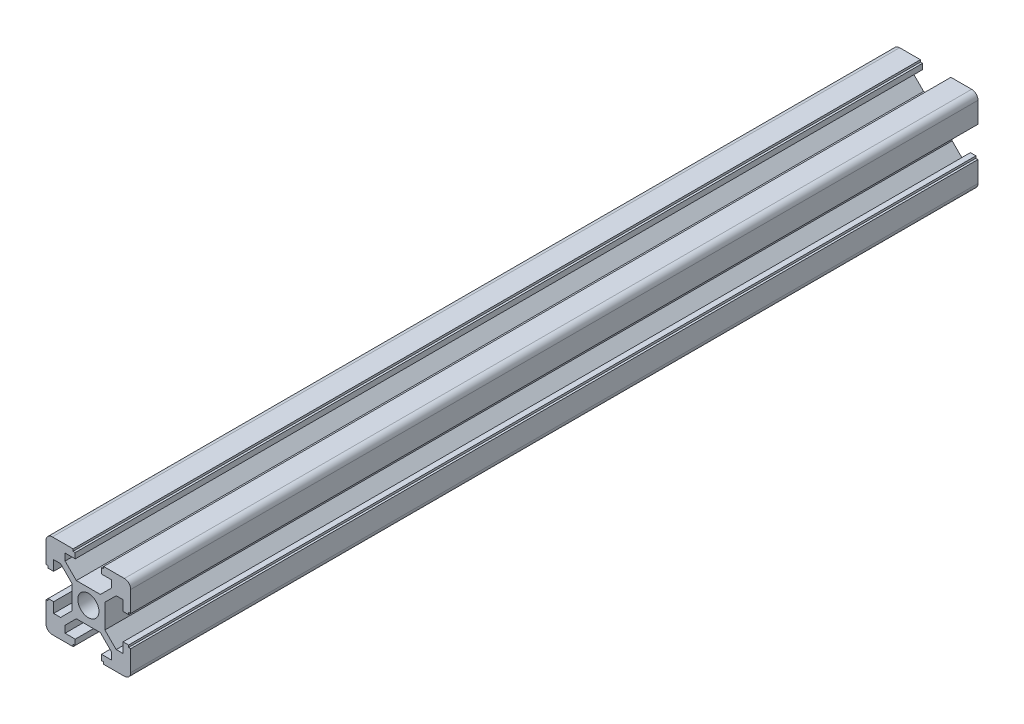
SolidWorks part; units mm, degrees
ref_plane "Front Plane" through (0, 0, 0) normal (0, 0, 1) x (1, 0, 0)
ref_plane "Top Plane" through (0, 0, 0) normal (0, 1, 0) x (1, 0, 0)
ref_plane "Right Plane" through (0, 0, 0) normal (1, 0, 0) x (0, 0, -1)
sketch "Sketch1" plane through (0, 0, 0) normal (0, 0, 1) x (1, 0, 0)
  line L0 (0, 13.3843) -> (0, -12.9126) construction
  line L1 (-14.4653, 0) -> (14.4653, 0) construction
  line L2 (2.8393, 3.9) -> (5.5, 6.5607)
  line L3 (-8.5, 10) -> (-3.6, 10)
  line L4 (-10, 8.5) -> (-10, 3.6)
  line L5 (-8.5, -10) -> (-3.6, -10)
  line L6 (10, 8.5) -> (10, 3.6)
  line L7 (-10, 10) -> (10, -10) construction
  line L8 (-10, -10) -> (10, 10) construction
  line L9 (-5.5, 8.2) -> (-3.1, 8.2)
  line L10 (-5.9626, 4.902) -> (-4.902, 5.9626) construction
  line L11 (-2.8393, 3.9) -> (-5.5, 6.5607)
  line L12 (-5.5, 8.2) -> (-5.5, 6.5607)
  line L13 (-2.8393, 3.9) -> (2.8393, 3.9)
  line L14 (5.5, 8.2) -> (5.5, 6.5607)
  line L15 (-3.1, 9.5) -> (-3.1, 8.2)
  line L16 (3.1, 9.5) -> (3.1, 8.2)
  line L17 (-3.1, 9.5) -> (3.1, 9.5) construction
  line L18 (-3.1, 9.5) -> (-3.6, 9.5)
  line L19 (-3.6, 9.5) -> (-3.6, 10)
  line L20 (3.1, 9.5) -> (3.6, 9.5)
  line L21 (3.6, 9.5) -> (3.6, 10)
  line L22 (3.6, 10) -> (8.5, 10)
  line L23 (3.1, 8.2) -> (5.5, 8.2)
  line L24 (-9.5, -3.1) -> (-9.5, -3.6)
  line L25 (-9.5, -3.6) -> (-10, -3.6)
  line L26 (-9.5, -3.1) -> (-8.2, -3.1)
  line L27 (-8.2, -3.1) -> (-8.2, -5.5)
  line L28 (-8.2, -5.5) -> (-6.5607, -5.5)
  line L29 (-3.9, -2.8393) -> (-6.5607, -5.5)
  line L30 (-3.9, 2.8393) -> (-3.9, -2.8393)
  line L31 (-3.9, 2.8393) -> (-6.5607, 5.5)
  line L32 (-8.2, 5.5) -> (-6.5607, 5.5)
  line L33 (-8.2, 5.5) -> (-8.2, 3.1)
  line L34 (-9.5, 3.1) -> (-8.2, 3.1)
  line L35 (-9.5, 3.1) -> (-9.5, 3.6)
  line L36 (-9.5, 3.6) -> (-10, 3.6)
  line L37 (-3.6, -9.5) -> (-3.6, -10)
  line L38 (-3.1, -9.5) -> (-3.6, -9.5)
  line L39 (-3.1, -9.5) -> (-3.1, -8.2)
  line L40 (-3.1, -8.2) -> (-5.5, -8.2)
  line L41 (-5.5, -8.2) -> (-5.5, -6.5607)
  line L42 (-2.8393, -3.9) -> (-5.5, -6.5607)
  line L43 (2.8393, -3.9) -> (-2.8393, -3.9)
  line L44 (2.8393, -3.9) -> (5.5, -6.5607)
  line L45 (5.5, -8.2) -> (5.5, -6.5607)
  line L46 (5.5, -8.2) -> (3.1, -8.2)
  line L47 (3.1, -9.5) -> (3.6, -9.5)
  line L48 (3.1, -9.5) -> (3.1, -8.2)
  line L49 (3.6, -9.5) -> (3.6, -10)
  line L50 (9.5, -3.6) -> (10, -3.6)
  line L51 (9.5, -3.1) -> (9.5, -3.6)
  line L52 (9.5, -3.1) -> (8.2, -3.1)
  line L53 (8.2, -5.5) -> (8.2, -3.1)
  line L54 (8.2, -5.5) -> (6.5607, -5.5)
  line L55 (3.9, -2.8393) -> (6.5607, -5.5)
  line L56 (3.9, -2.8393) -> (3.9, 2.8393)
  line L57 (3.9, 2.8393) -> (6.5607, 5.5)
  line L58 (8.2, 5.5) -> (6.5607, 5.5)
  line L59 (8.2, 3.1) -> (8.2, 5.5)
  line L60 (9.5, 3.1) -> (8.2, 3.1)
  line L61 (9.5, 3.1) -> (9.5, 3.6)
  line L62 (9.5, 3.6) -> (10, 3.6)
  line L63 (-10, -3.6) -> (-10, -8.5)
  line L64 (3.6, -10) -> (8.5, -10)
  line L65 (10, -3.6) -> (10, -8.5)
  arc A0 (8.5, 10) -> (10, 8.5) centre (8.5, 8.5) cw
  arc A1 (8.5, -10) -> (10, -8.5) centre (8.5, -8.5) ccw
  arc A2 (-10, -8.5) -> (-8.5, -10) centre (-8.5, -8.5) ccw
  arc A3 (-8.5, 10) -> (-10, 8.5) centre (-8.5, 8.5) ccw
  circle A4 centre (0, 0.2358) radius 2.5
  point P5 (0, 0)
  point P30 (-5.4323, 5.4323)
  point P38 (0, 9.5)
  dimension "D3" = 1.5
  dimension "D15" = 5
  dimension "D1" = 20
  dimension "D2" = 20
  dimension "D4" = 6.2
  dimension "D5" = 11
  dimension "D6" = 1.8
  dimension "D7" = 1.5
  dimension "D8" = 90
  dimension "D9" = 0.5
  dimension "D10" = 0.5
  dimension "D11" = 0.5
  dimension "D12" = 0.5
  dimension "D13" = 6.1
  dimension "D14" = 45
extrude "Boss-Extrude1" add sketch "Sketch1" along normal blind 200
